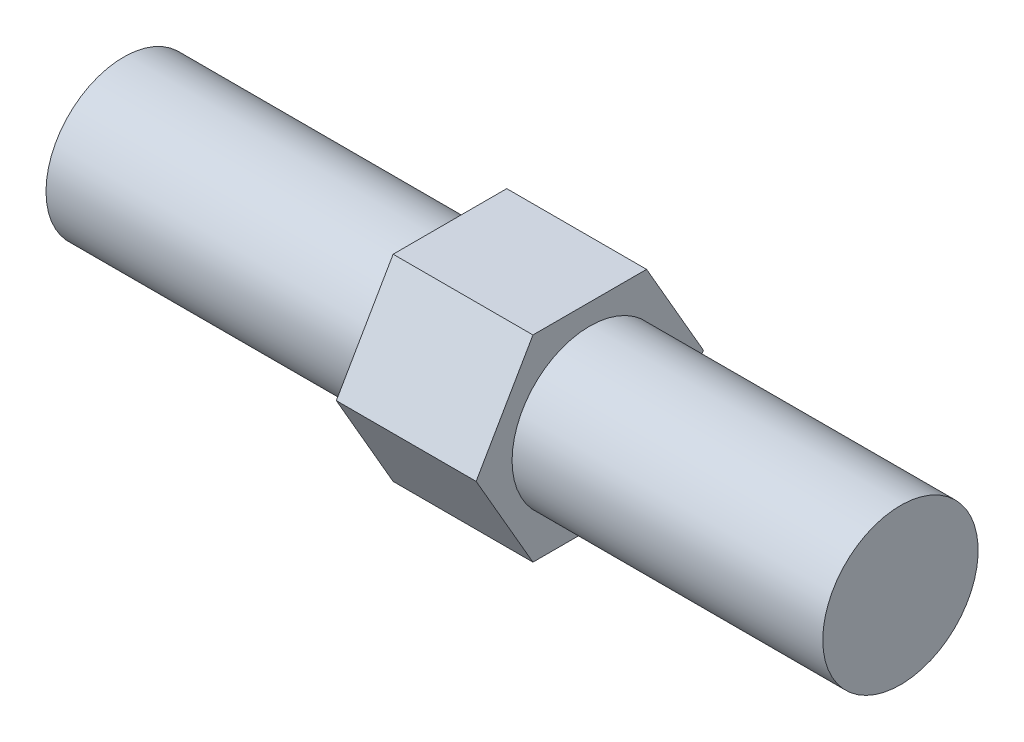
SolidWorks part; units mm, degrees
ref_plane "Front Plane" through (0, 0, 0) normal (0, 0, 1) x (1, 0, 0)
ref_plane "Top Plane" through (0, 0, 0) normal (0, 1, 0) x (1, 0, 0)
ref_plane "Right Plane" through (0, 0, 0) normal (1, 0, 0) x (0, 0, -1)
sketch "Sketch1" plane through (0, 0, 0) normal (0, 1, 0) x (1, 0, 0)
  line L0 (-19.5531, 0) -> (18.2716, 0) construction
  line L1 (-7.5, 0) -> (-7.5, 1.5)
  line L2 (-7.5, 1.5) -> (7.5, 1.5)
  line L3 (7.5, 1.5) -> (7.5, 0)
  line L4 (7.5, 0) -> (-7.5, 0)
  point P5 (0, 0)
  dimension "D1" = 3
  dimension "D2" = 15
revolve "Revolve1" add sketch "Sketch1" angle 360 about L0
cosmetic thread "Cosmetic Thread1" parameters "D2"=2.459
cosmetic thread "Cosmetic Thread2" parameters "D2"=2.013
sketch "Sketch2" plane through (0, 0, 0) normal (1, 0, 0) x (0, 0, -1)
  line L1 (2.1939, 0) -> (1.097, 1.9)
  line L2 (1.097, 1.9) -> (-1.097, 1.9)
  line L3 (-1.097, 1.9) -> (-2.1939, 0)
  line L4 (-2.1939, 0) -> (-1.097, -1.9)
  line L5 (-1.097, -1.9) -> (1.097, -1.9)
  line L6 (1.097, -1.9) -> (2.1939, 0)
  circle A0 centre (0, 0) radius 1.9 construction
  dimension "D1" = 3.8
extrude "Boss-Extrude1" add sketch "Sketch2" along normal blind 1.5 and the other way blind 1.2
